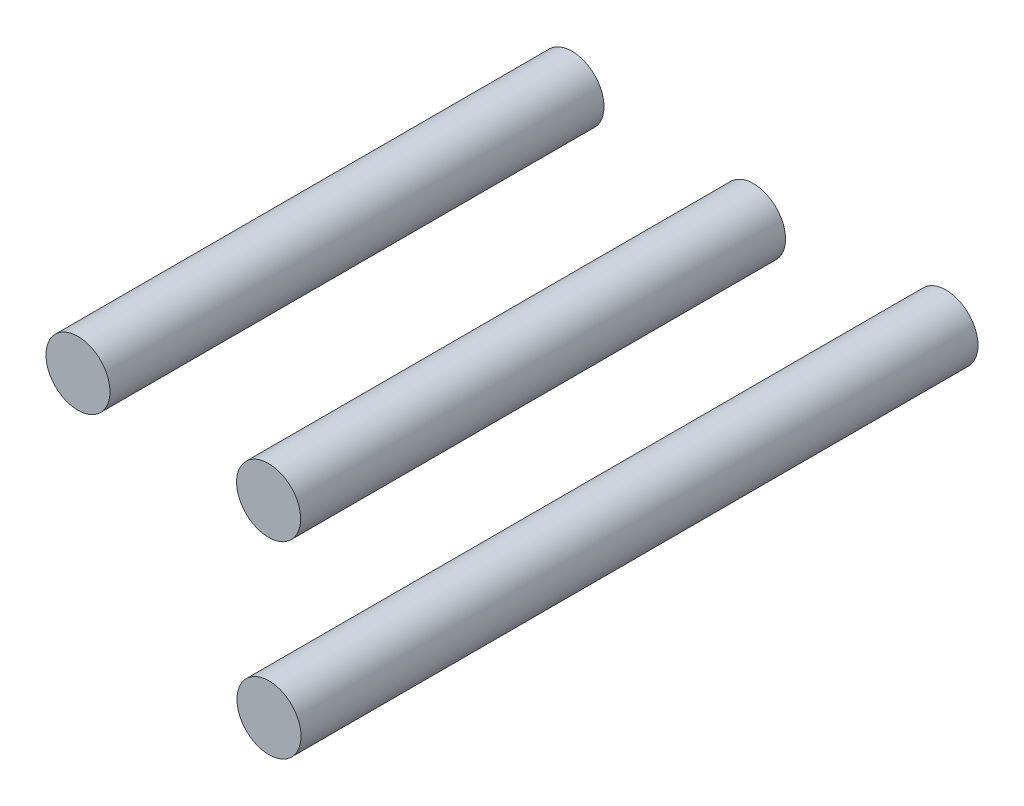
SolidWorks part; units mm, degrees
ref_plane "Front Plane" through (0, 0, 0) normal (0, 0, 1) x (1, 0, 0)
ref_plane "Top Plane" through (0, 0, 0) normal (0, 1, 0) x (1, 0, 0)
ref_plane "Right Plane" through (0, 0, 0) normal (1, 0, 0) x (0, 0, -1)
sketch "Sketch1" plane through (0, 0, 0) normal (0, 0, 1) x (1, 0, 0)
  circle A0 centre (-61.1522, -5.292) radius 3.5
  dimension "D1" = 7
extrude "Boss-Extrude1" add sketch "Sketch1" along normal blind 54
sketch "Sketch2" plane through (0, 0, 0) normal (0, 0, 1) x (1, 0, 0)
  circle A0 centre (-41.3151, -7.9055) radius 3.5
  dimension "D1" = 7
extrude "Boss-Extrude2" add sketch "Sketch2" along normal blind 53 separate body
sketch "Sketch3" plane through (0, 0, 0) normal (0, 0, 1) x (1, 0, 0)
  circle A0 centre (-20.2737, -7.4576) radius 3.5
  dimension "D1" = 7
extrude "Boss-Extrude3" add sketch "Sketch3" along normal blind 74 separate body
